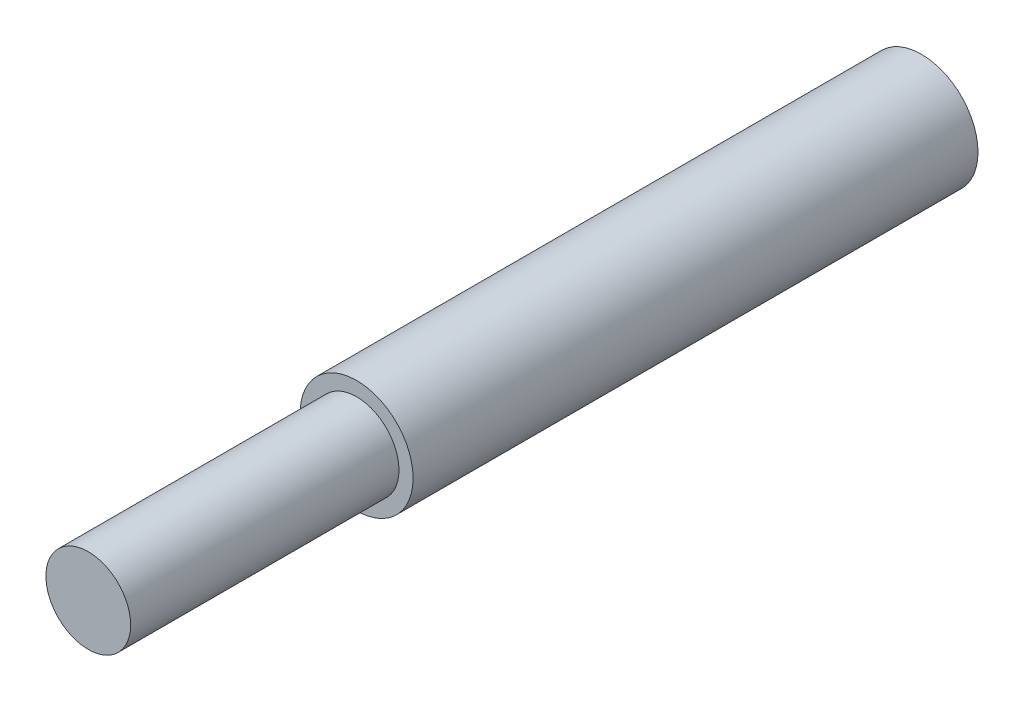
SolidWorks part; units mm, degrees
ref_plane "Front Plane" through (0, 0, 0) normal (0, 0, 1) x (1, 0, 0)
ref_plane "Top Plane" through (0, 0, 0) normal (0, 1, 0) x (1, 0, 0)
ref_plane "Right Plane" through (0, 0, 0) normal (1, 0, 0) x (0, 0, -1)
sketch "S01 - Ground 8 mm sliding surface" plane through (0, 0, 0) normal (0, 0, 1) x (1, 0, 0)
  circle A0 centre (0, 0) radius 4
  dimension "D1" = 8
extrude "01 - Ground 8 mm sliding surface" add sketch "S01 - Ground 8 mm sliding surface" along normal blind 40
sketch "S02 - M6 retaining thread envelope" plane through (0, 0, 0) normal (0, 0, 1) x (1, 0, 0)
  circle A0 centre (0, 0) radius 3
  dimension "D1" = 6
extrude "02 - M6 retaining thread envelope" add sketch "S02 - M6 retaining thread envelope" along normal blind 19 from offset 40
